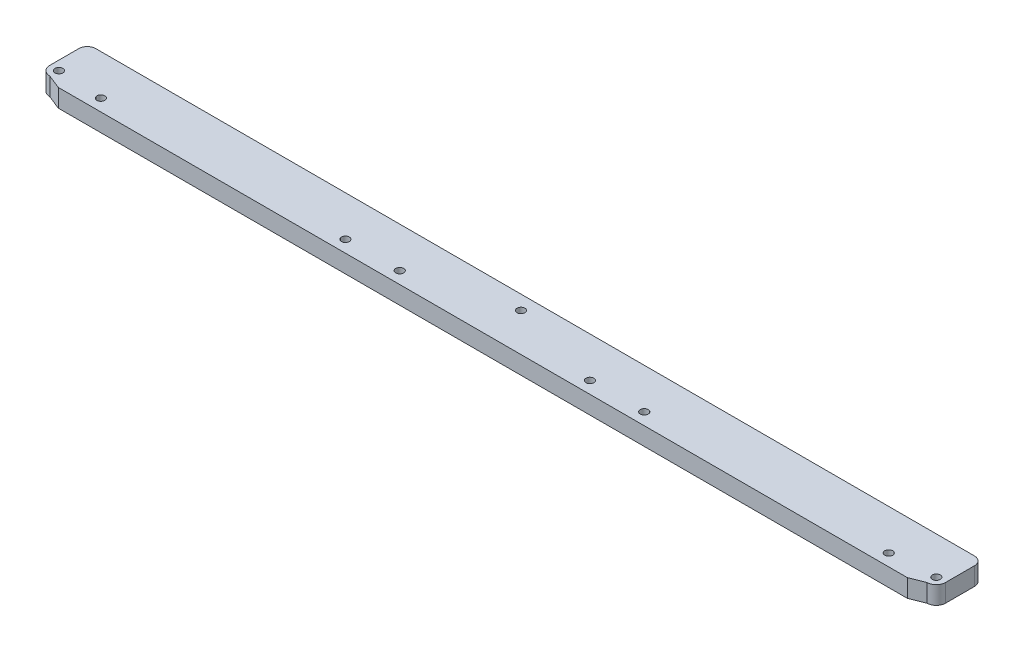
SolidWorks part; units mm, degrees
ref_plane "Front Plane" through (0, 0, 0) normal (0, 0, 1) x (1, 0, 0)
ref_plane "Top Plane" through (0, 0, 0) normal (0, 1, 0) x (1, 0, 0)
ref_plane "Right Plane" through (0, 0, 0) normal (1, 0, 0) x (0, 0, -1)
sketch "Sketch1" plane through (0, 0, 0) normal (0, 1, 0) x (1, 0, 0)
  line L0 (-158.25, 0) -> (-158.25, 13.25)
  line L1 (-150, 3.25) -> (150, 3.25)
  line L2 (-150, 3.25) -> (-150, -3.25)
  line L3 (-150, -3.25) -> (150, -3.25)
  line L4 (150, 3.25) -> (150, -3.25)
  line L5 (-150, 3.25) -> (-155, 3.25)
  line L6 (-150, 3.25) -> (-150, -3.25)
  line L7 (-150, -3.25) -> (-155, -3.25)
  line L8 (-155, 3.25) -> (-155, -3.25)
  line L9 (150, 3.25) -> (155, 3.25)
  line L10 (150, 3.25) -> (150, -3.25)
  line L11 (150, -3.25) -> (155, -3.25)
  line L12 (155, 3.25) -> (155, -3.25)
  line L13 (-158.25, 13.25) -> (158.25, 13.25)
  line L14 (158.25, 13.25) -> (158.25, 0)
  line L15 (-150, -3.25) -> (-150, -5.25)
  line L16 (-150, -5.25) -> (150, -5.25)
  line L17 (150, -5.25) -> (150, -3.25)
  line L18 (-150, -5.25) -> (-155, -3.25)
  line L19 (150, -5.25) -> (155, -3.25)
  circle A0 centre (-155, 0) radius 1.4
  circle A1 centre (155, 0) radius 1.4
  arc A2 (155, 3.25) -> (155, -3.25) centre (155, 0) cw
  arc A3 (-155, 3.25) -> (-155, -3.25) centre (-155, 0) ccw
  circle A4 centre (0, 8.25) radius 1.4
  point P4 (0, 3.25)
  point P5 (-150, 0)
  dimension "D3" = 2.8
  dimension "D1" = 6.5
  dimension "D2" = 300
  dimension "D4" = 5
  dimension "D5" = 5
  dimension "D6" = 5
  dimension "D7" = 2
extrude "Boss-Extrude1" add sketch "Sketch1" along normal blind 6.35 contours L8 A3 A0 | A0 L8 L7 L2 L5 | L4 L1 L2 L3 | A1 L12 L9 L4 L11 | A2 L12 A1 | A3 L5 L1 L9 A2 L14 L13 L0 A4 | L16 L17 L3 L15 | L17 L19 L11 | L18 L15 L7
fillet "Fillet1" radius 3 2 edges at (158.25, 3.175, -13.25) (-158.25, 3.175, -13.25)
sketch "Sketch2" plane through (0, 6.35, 0) normal (0, 1, 0) x (1, 0, 0)
  line L0 (0, 13.25) -> (0, -5.25) construction
  line L1 (-155.25, 13.25) -> (155.25, 13.25) construction
  line L3 (-150, -5.25) -> (150, -5.25) construction
  circle A0 centre (-33.6, -1) radius 1.4
  circle A1 centre (-52.8, -1) radius 1.4
  circle A2 centre (-139.2, -1) radius 1.4
  circle A3 centre (139.2, -1) radius 1.4
  circle A4 centre (52.8, -1) radius 1.4
  circle A5 centre (33.6, -1) radius 1.4
  dimension "D1" = 2.8
  dimension "D3" = 67.2
  dimension "D2" = 86.4
  dimension "D4" = 19.2
  dimension "D5" = 2.25
extrude "Cut-Extrude1" cut sketch "Sketch2" against normal through all
